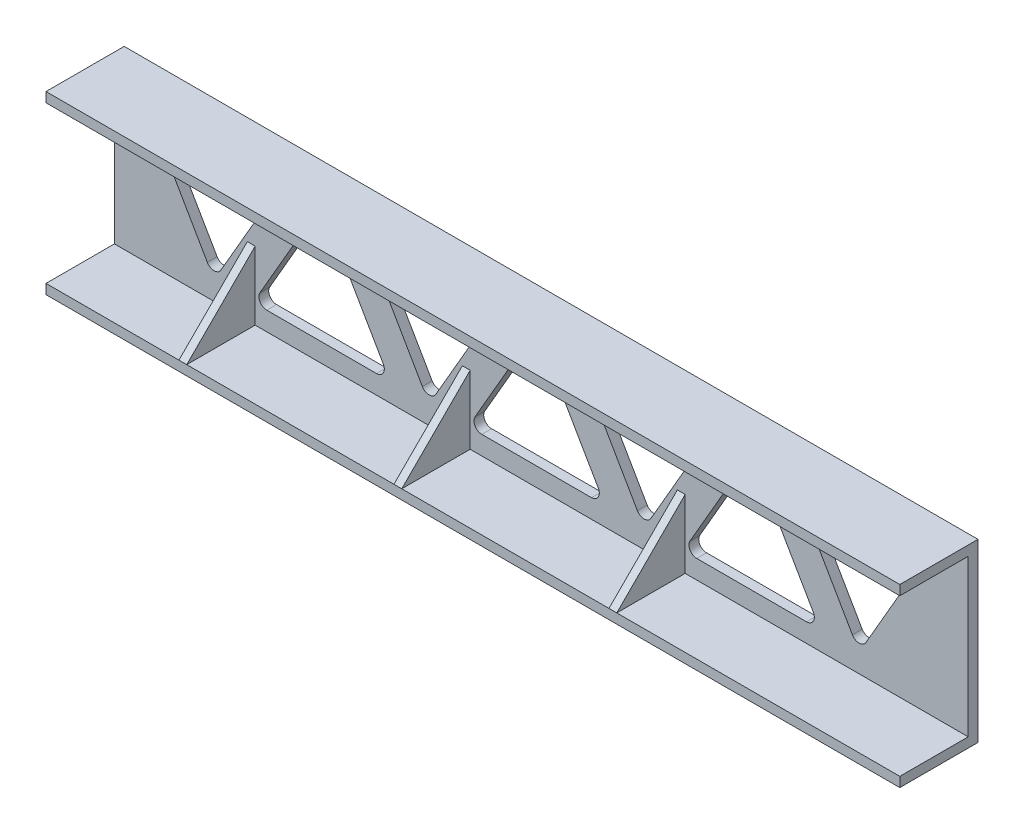
SolidWorks part; units mm, degrees
ref_plane "Front Plane" through (0, 0, 0) normal (0, 0, 1) x (1, 0, 0)
ref_plane "Top Plane" through (0, 0, 0) normal (0, 1, 0) x (1, 0, 0)
ref_plane "Right Plane" through (0, 0, 0) normal (1, 0, 0) x (0, 0, -1)
sketch "Sketch1" plane through (0, 0, 0) normal (0, 0, 1) x (1, 0, 0)
  line L1 (277.368, 0) -> (277.368, 57.15)
  line L2 (277.368, 57.15) -> (0, 57.15)
  line L3 (0, 57.15) -> (0, 0)
  line L4 (0, 0) -> (277.368, 0)
  line L5 (30.1853, 13.081) -> (12.3597, 43.9558)
  line L6 (14.5594, 47.7658) -> (50.2106, 47.7658)
  line L7 (52.4103, 43.9558) -> (34.5847, 13.081)
  line L8 (32.385, 9.271) -> (45.085, 9.271) construction
  line L9 (49.4844, 9.271) -> (85.1356, 9.271)
  line L10 (87.3353, 13.081) -> (69.5097, 43.9558)
  line L11 (65.1103, 43.9558) -> (47.2847, 13.081)
  line L12 (100.0353, 13.081) -> (82.2097, 43.9558)
  line L13 (84.4094, 47.7658) -> (120.0606, 47.7658)
  line L14 (122.2603, 43.9558) -> (104.4347, 13.081)
  line L15 (102.235, 9.271) -> (114.935, 9.271) construction
  line L16 (119.3344, 9.271) -> (154.9856, 9.271)
  line L17 (157.1853, 13.081) -> (139.3597, 43.9558)
  line L18 (134.9603, 43.9558) -> (117.1347, 13.081)
  line L19 (169.8853, 13.081) -> (152.0597, 43.9558)
  line L20 (154.2594, 47.7658) -> (189.9106, 47.7658)
  line L21 (192.1103, 43.9558) -> (174.2847, 13.081)
  line L22 (172.085, 9.271) -> (184.785, 9.271) construction
  line L23 (189.1844, 9.271) -> (224.8356, 9.271)
  line L24 (227.0353, 13.081) -> (209.2097, 43.9558)
  line L25 (204.8103, 43.9558) -> (186.9847, 13.081)
  line L26 (239.7353, 13.081) -> (221.9097, 43.9558)
  line L27 (224.1094, 47.7658) -> (259.7606, 47.7658)
  line L28 (261.9603, 43.9558) -> (244.1347, 13.081)
  line L29 (241.935, 9.271) -> (252.095, 9.271) construction
  arc A0 (259.7606, 47.7658) -> (261.9603, 43.9558) centre (259.7606, 45.2258) cw
  arc A1 (221.9097, 43.9558) -> (224.1094, 47.7658) centre (224.1094, 45.2258) cw
  arc A2 (239.7353, 13.081) -> (244.1347, 13.081) centre (241.935, 14.351) ccw
  arc A3 (189.1844, 9.271) -> (186.9847, 13.081) centre (189.1844, 11.811) cw
  arc A4 (224.8356, 9.271) -> (227.0353, 13.081) centre (224.8356, 11.811) ccw
  arc A5 (209.2097, 43.9558) -> (204.8103, 43.9558) centre (207.01, 42.6858) ccw
  arc A6 (189.9106, 47.7658) -> (192.1103, 43.9558) centre (189.9106, 45.2258) cw
  arc A7 (152.0597, 43.9558) -> (154.2594, 47.7658) centre (154.2594, 45.2258) cw
  arc A8 (169.8853, 13.081) -> (174.2847, 13.081) centre (172.085, 14.351) ccw
  arc A9 (154.9856, 9.271) -> (157.1853, 13.081) centre (154.9856, 11.811) ccw
  arc A10 (119.3344, 9.271) -> (117.1347, 13.081) centre (119.3344, 11.811) cw
  arc A11 (139.3597, 43.9558) -> (134.9603, 43.9558) centre (137.16, 42.6858) ccw
  arc A12 (120.0606, 47.7658) -> (122.2603, 43.9558) centre (120.0606, 45.2258) cw
  arc A13 (82.2097, 43.9558) -> (84.4094, 47.7658) centre (84.4094, 45.2258) cw
  arc A14 (100.0353, 13.081) -> (104.4347, 13.081) centre (102.235, 14.351) ccw
  arc A15 (47.2847, 13.081) -> (49.4844, 9.271) centre (49.4844, 11.811) ccw
  arc A16 (69.5097, 43.9558) -> (65.1103, 43.9558) centre (67.31, 42.6858) ccw
  arc A17 (85.1356, 9.271) -> (87.3353, 13.081) centre (85.1356, 11.811) ccw
  arc A18 (34.5847, 13.081) -> (30.1853, 13.081) centre (32.385, 14.351) cw
  arc A19 (50.2106, 47.7658) -> (52.4103, 43.9558) centre (50.2106, 45.2258) cw
  arc A20 (12.3597, 43.9558) -> (14.5594, 47.7658) centre (14.5594, 45.2258) cw
  point P23 (0, 0)
  point P30 (264.16, 47.7658)
  point P33 (219.71, 47.7658)
  point P42 (229.235, 9.271)
  point P45 (207.01, 47.7658)
  point P48 (194.31, 47.7658)
  point P51 (149.86, 47.7658)
  point P57 (159.385, 9.271)
  point P63 (137.16, 47.7658)
  point P66 (124.46, 47.7658)
  point P69 (80.01, 47.7658)
  point P78 (67.31, 47.7658)
  point P81 (89.535, 9.271)
  point P87 (54.61, 47.7658)
  point P90 (10.16, 47.7658)
  dimension "D35" = 2.54
  dimension "D1" = 44.45
  dimension "D2" = 44.45
  dimension "D3" = 44.45
  dimension "D4" = 10.16
  dimension "D5" = 9.271
  dimension "D6" = 57.15
  dimension "D7" = 44.45
  dimension "D8" = 44.45
  dimension "D9" = 44.45
  dimension "D10" = 12.7
  dimension "D11" = 277.368
  dimension "D12" = 44.45
  dimension "D13" = 44.45
  dimension "D14" = 44.45
  dimension "D15" = 44.45
  dimension "D16" = 44.45
  dimension "D17" = 12.7
  dimension "D18" = 44.45
  dimension "D19" = 44.45
  dimension "D20" = 44.45
  dimension "D21" = 44.45
  dimension "D22" = 44.45
  dimension "D23" = 12.7
  dimension "D24" = 9.271
  dimension "D25" = 12.7
  dimension "D26" = 9.271
  dimension "D27" = 12.7
  dimension "D28" = 44.45
  dimension "D29" = 44.45
  dimension "D30" = 10.16
  dimension "D31" = 9.271
  dimension "D32" = 12.7
  dimension "D33" = 44.45
  dimension "D34" = 44.45
  dimension "D36" = 44.45
extrude "Boss-Extrude1" add sketch "Sketch1" along normal blind 3.175
sketch "Sketch2" plane through (0, 57.15, 0) normal (0, 1, 0) x (1, 0, 0)
  line L0 (0, 0) -> (0, -25.4)
  line L1 (0, -25.4) -> (277.368, -25.4)
  line L2 (277.368, -25.4) -> (277.368, 0)
  line L3 (277.368, 0) -> (0, 0)
  dimension "D1" = 25.4
extrude "Boss-Extrude2" add sketch "Sketch2" against normal blind 3.175
sketch "Sketch3" plane through (0, 0, 0) normal (0, -1, 0) x (1, 0, 0)
  line L0 (0, 0) -> (0, 25.4)
  line L1 (0, 25.4) -> (277.368, 25.4)
  line L2 (277.368, 25.4) -> (277.368, 0)
  line L3 (277.368, 0) -> (0, 0)
extrude "Boss-Extrude3" add sketch "Sketch3" against normal blind 3.175
sketch "Sketch4" plane through (0, 0, 3.175) normal (0, 0, 1) x (1, 0, 0)
  line L0 (0, 3.175) -> (277.368, 3.175) construction
  line L1 (0, 3.175) -> (43.18, 3.175) construction
  line L2 (43.18, 3.175) -> (113.03, 3.175) construction
  line L3 (113.03, 3.175) -> (182.88, 3.175) construction
  line L4 (277.368, 53.975) -> (0, 53.975) construction
  line L5 (0, 53.975) -> (76.708, 53.975) construction
  line L6 (76.708, 53.975) -> (146.558, 53.975) construction
  line L7 (146.558, 53.975) -> (216.408, 53.975) construction
  line L8 (43.18, 3.175) -> (43.18, 20.447) construction
  line L9 (113.03, 3.175) -> (113.03, 20.447) construction
  line L10 (182.88, 3.175) -> (182.88, 20.447) construction
  line L11 (216.408, 53.975) -> (216.408, 36.703) construction
  line L12 (146.558, 53.975) -> (146.558, 36.703) construction
  line L13 (76.708, 53.975) -> (76.708, 36.703) construction
  line L14 (277.368, 3.175) -> (277.368, 53.975) construction
  line L15 (0, 53.975) -> (0, 3.175) construction
  point P24 (113.03, 11.811)
  dimension "D1" = 69.85
  dimension "D2" = 69.85
  dimension "D3" = 60.96
  dimension "D4" = 43.18
  dimension "D5" = 69.85
  dimension "D6" = 69.85
ref_plane "Plane1" through (43.18, 0, 0) normal (1, 0, 0) x (0, 1, 0)
ref_plane "Plane2" through (113.03, 0, 0) normal (1, 0, 0) x (0, 1, 0)
ref_plane "Plane3" through (182.88, 0, 0) normal (1, 0, 0) x (0, 1, 0)
ref_plane "Plane4" through (216.408, 0, 0) normal (-1, 0, 0) x (0, -1, 0)
ref_plane "Plane5" through (146.558, 0, 0) normal (-1, 0, 0) x (0, -1, 0)
ref_plane "Plane6" through (76.708, 0, 0) normal (-1, 0, 0) x (0, -1, 0)
sketch "Sketch5" plane through (43.18, 0, 0) normal (1, 0, 0) x (0, 1, 0)
  line L0 (3.175, 3.175) -> (3.175, 25.4)
  line L1 (3.175, 3.175) -> (25.4, 3.175)
  line L2 (3.175, 3.175) -> (53.975, 3.175) construction
  line L3 (25.4, 3.175) -> (3.175, 25.4)
  dimension "D1" = 22.225
  dimension "D2" = 22.225
extrude "Boss-Extrude4" add sketch "Sketch5" along normal blind 2.54
sketch "Sketch6" plane through (113.03, 0, 0) normal (1, 0, 0) x (0, 1, 0)
  line L0 (3.175, 25.4) -> (3.175, 3.175)
  line L1 (3.175, 3.175) -> (25.4, 3.175)
  line L2 (25.4, 3.175) -> (3.175, 25.4)
extrude "Boss-Extrude5" add sketch "Sketch6" along normal blind 2.54
sketch "Sketch7" plane through (182.88, 0, 0) normal (1, 0, 0) x (0, 1, 0)
  line L0 (3.175, 25.4) -> (3.175, 3.175)
  line L1 (3.175, 3.175) -> (25.4, 3.175)
  line L2 (25.4, 3.175) -> (3.175, 25.4)
extrude "Boss-Extrude6" add sketch "Sketch7" along normal blind 2.54
sketch "Sketch8" plane through (76.708, 0, 0) normal (-1, 0, 0) x (0, -1, 0)
  line L0 (-53.975, 3.175) -> (-53.975, 25.4)
  line L1 (-53.975, 25.4) -> (-31.75, 3.175)
  line L2 (-3.175, 3.175) -> (-53.975, 3.175) construction
  line L3 (-31.75, 3.175) -> (-53.975, 3.175)
extrude "Boss-Extrude7" add sketch "Sketch8" against normal blind 2.54
sketch "Sketch9" plane through (146.558, 0, 0) normal (-1, 0, 0) x (0, -1, 0)
  line L0 (-53.975, 25.4) -> (-53.975, 3.175)
  line L1 (-53.975, 3.175) -> (-31.75, 3.175)
  line L2 (-31.75, 3.175) -> (-53.975, 25.4)
extrude "Boss-Extrude8" add sketch "Sketch9" against normal blind 2.54
sketch "Sketch10" plane through (216.408, 0, 0) normal (-1, 0, 0) x (0, -1, 0)
  line L0 (-53.975, 25.4) -> (-53.975, 3.175)
  line L1 (-53.975, 3.175) -> (-31.75, 3.175)
  line L2 (-31.75, 3.175) -> (-53.975, 25.4)
extrude "Boss-Extrude9" add sketch "Sketch10" against normal blind 2.54
